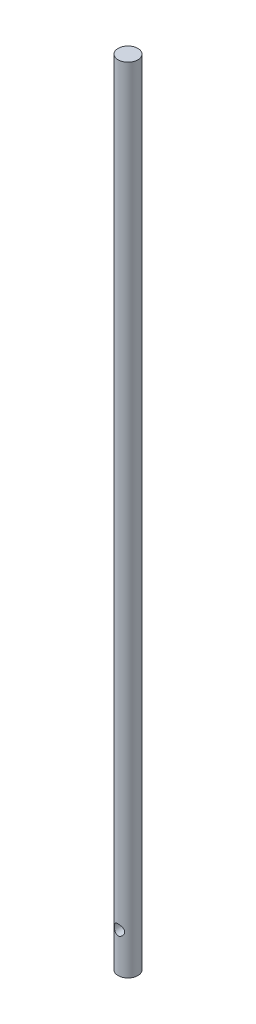
SolidWorks part; units mm, degrees
material "Plain Carbon Steel"
ref_plane "Front Plane" through (0, 0, 0) normal (0, 0, 1) x (1, 0, 0)
ref_plane "Top Plane" through (0, 0, 0) normal (0, 1, 0) x (1, 0, 0)
ref_plane "Right Plane" through (0, 0, 0) normal (1, 0, 0) x (0, 0, -1)
sketch "Sketch1" plane through (0, 0, 0) normal (0, 1, 0) x (1, 0, 0)
  circle A0 centre (0, 0) radius 2.5
  dimension "D1" = 5
extrude "Boss-Extrude1" add sketch "Sketch1" along normal blind 200
sketch "Sketch2" plane through (0, 0, 0) normal (0, 0, 1) x (1, 0, 0)
  line L0 (0, 200) -> (0, 0) construction
  circle A0 centre (0, 10) radius 1.3
  point P2 (0, 5.9372)
  point P4 (-1.3866, 9.9034)
  dimension "D1" = 2.6
  dimension "D2" = 10
extrude "Cut-Extrude1" cut sketch "Sketch2" against normal through all both and the other way through all
other "Bounding Box"
ref_plane "Default Plane" through (0.3081, 0, -3.5221) normal (-0.766, 0, 0.6428) x (0.6428, 0, 0.766)
